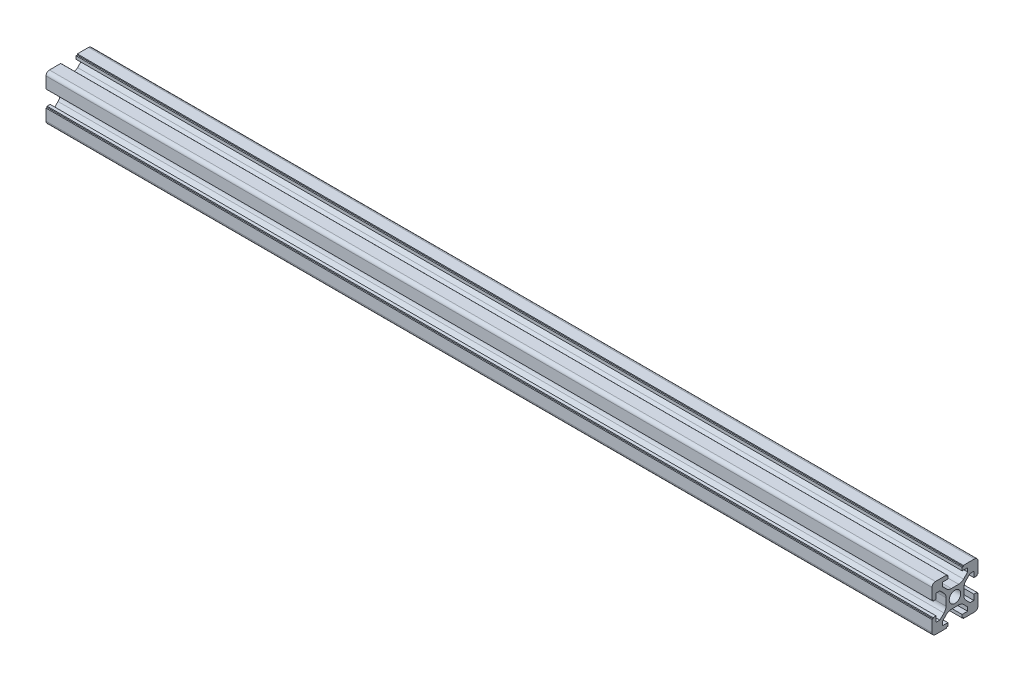
SolidWorks part; units mm, degrees
ref_plane "前视基准面" through (0, 0, 0) normal (0, 0, 1) x (1, 0, 0)
ref_plane "上视基准面" through (0, 0, 0) normal (0, 1, 0) x (1, 0, 0)
ref_plane "右视基准面" through (0, 0, 0) normal (1, 0, 0) x (0, 0, -1)
sketch "草图1" plane through (0, 0, 0) normal (1, 0, 0) x (0, 0, -1)
  line L0 (0, 0) -> (-10, 0) construction
  line L1 (0, 0) -> (0, 10) construction
  line L2 (0, 0) -> (-10, 10) construction
  line L3 (-10, 10) -> (-10, 3.6)
  line L4 (-10, 3.6) -> (-9.531, 3.6)
  line L5 (-9.531, 3.6) -> (-9.531, 3.1)
  line L6 (-9.531, 3.1) -> (-8.2, 3.1)
  line L7 (-8.2, 3.1) -> (-8.2, 5.5)
  line L8 (-8.2, 5.5) -> (-6.5607, 5.5)
  line L9 (-6.5607, 5.5) -> (-3.9, 2.8393)
  line L10 (-3.9, 2.8393) -> (-3.9, 0)
  line L11 (-3.6, 9.531) -> (-3.1, 9.531)
  line L12 (-2.8393, 3.9) -> (0, 3.9)
  line L13 (-5.5, 6.5607) -> (-2.8393, 3.9)
  line L14 (-5.5, 8.2) -> (-5.5, 6.5607)
  line L15 (-3.1, 8.2) -> (-5.5, 8.2)
  line L16 (-3.1, 9.531) -> (-3.1, 8.2)
  line L17 (-3.6, 10) -> (-3.6, 9.531)
  line L18 (-10, 10) -> (-3.6, 10)
  line L19 (0, 0) -> (0, 10) construction
  line L20 (0, 0) -> (10, 0) construction
  line L21 (0, 0) -> (10, 10) construction
  line L22 (10, 10) -> (3.6, 10)
  line L23 (3.6, 10) -> (3.6, 9.531)
  line L24 (3.6, 9.531) -> (3.1, 9.531)
  line L25 (3.1, 9.531) -> (3.1, 8.2)
  line L26 (3.1, 8.2) -> (5.5, 8.2)
  line L27 (5.5, 8.2) -> (5.5, 6.5607)
  line L28 (5.5, 6.5607) -> (2.8393, 3.9)
  line L29 (2.8393, 3.9) -> (0, 3.9)
  line L30 (9.531, 3.6) -> (9.531, 3.1)
  line L31 (3.9, 2.8393) -> (3.9, 0)
  line L32 (6.5607, 5.5) -> (3.9, 2.8393)
  line L33 (8.2, 5.5) -> (6.5607, 5.5)
  line L34 (8.2, 3.1) -> (8.2, 5.5)
  line L35 (9.531, 3.1) -> (8.2, 3.1)
  line L36 (10, 3.6) -> (9.531, 3.6)
  line L37 (10, 10) -> (10, 3.6)
  line L38 (0, 0) -> (10, 0) construction
  line L39 (0, 0) -> (0, -10) construction
  line L40 (0, 0) -> (10, -10) construction
  line L41 (10, -10) -> (10, -3.6)
  line L42 (10, -3.6) -> (9.531, -3.6)
  line L43 (9.531, -3.6) -> (9.531, -3.1)
  line L44 (9.531, -3.1) -> (8.2, -3.1)
  line L45 (8.2, -3.1) -> (8.2, -5.5)
  line L46 (8.2, -5.5) -> (6.5607, -5.5)
  line L47 (6.5607, -5.5) -> (3.9, -2.8393)
  line L48 (3.9, -2.8393) -> (3.9, 0)
  line L49 (3.6, -9.531) -> (3.1, -9.531)
  line L50 (2.8393, -3.9) -> (0, -3.9)
  line L51 (5.5, -6.5607) -> (2.8393, -3.9)
  line L52 (5.5, -8.2) -> (5.5, -6.5607)
  line L53 (3.1, -8.2) -> (5.5, -8.2)
  line L54 (3.1, -9.531) -> (3.1, -8.2)
  line L55 (3.6, -10) -> (3.6, -9.531)
  line L56 (10, -10) -> (3.6, -10)
  line L57 (0, 0) -> (0, -10) construction
  line L58 (0, 0) -> (-10, 0) construction
  line L59 (0, 0) -> (-10, -10) construction
  line L60 (-10, -10) -> (-3.6, -10)
  line L61 (-3.6, -10) -> (-3.6, -9.531)
  line L62 (-3.6, -9.531) -> (-3.1, -9.531)
  line L63 (-3.1, -9.531) -> (-3.1, -8.2)
  line L64 (-3.1, -8.2) -> (-5.5, -8.2)
  line L65 (-5.5, -8.2) -> (-5.5, -6.5607)
  line L66 (-5.5, -6.5607) -> (-2.8393, -3.9)
  line L67 (-2.8393, -3.9) -> (0, -3.9)
  line L68 (-9.531, -3.6) -> (-9.531, -3.1)
  line L69 (-3.9, -2.8393) -> (-3.9, 0)
  line L70 (-6.5607, -5.5) -> (-3.9, -2.8393)
  line L71 (-8.2, -5.5) -> (-6.5607, -5.5)
  line L72 (-8.2, -3.1) -> (-8.2, -5.5)
  line L73 (-9.531, -3.1) -> (-8.2, -3.1)
  line L74 (-10, -3.6) -> (-9.531, -3.6)
  line L75 (-10, -10) -> (-10, -3.6)
  arc A0 (0, 2.5) -> (-2.5, 0) centre (0, 0) ccw
  arc A1 (2.5, 0) -> (0, 2.5) centre (0, 0) ccw
  arc A2 (0, -2.5) -> (2.5, 0) centre (0, 0) ccw
  arc A3 (-2.5, 0) -> (0, -2.5) centre (0, 0) ccw
  point P89 (0, 0)
  dimension "D3" = 5
  dimension "D1" = 10
  dimension "D2" = 10
  dimension "D4" = 10
  dimension "D5" = 1.8
  dimension "D6" = 5.5
  dimension "D7" = 3.1
  dimension "D8" = 3.6
  dimension "D9" = 6.1
  dimension "D10" = 0.75
  dimension "D11" = 4
extrude "凸台-拉伸1" add sketch "草图1" along normal blind 385
fillet "圆角1" radius 1.5 4 edges at (192.5, -10, -10) (192.5, -10, 10) (192.5, 10, -10) (192.5, 10, 10)
fillet "圆角2" radius 3 8 edges at (192.5, -3.9, 2.8393) (192.5, -3.9, -2.8393) (192.5, -2.8393, -3.9) (192.5, 2.8393, -3.9) (192.5, 2.8393, 3.9) (192.5, -2.8393, 3.9) (192.5, 3.9, 2.8393) (192.5, 3.9, -2.8393)
